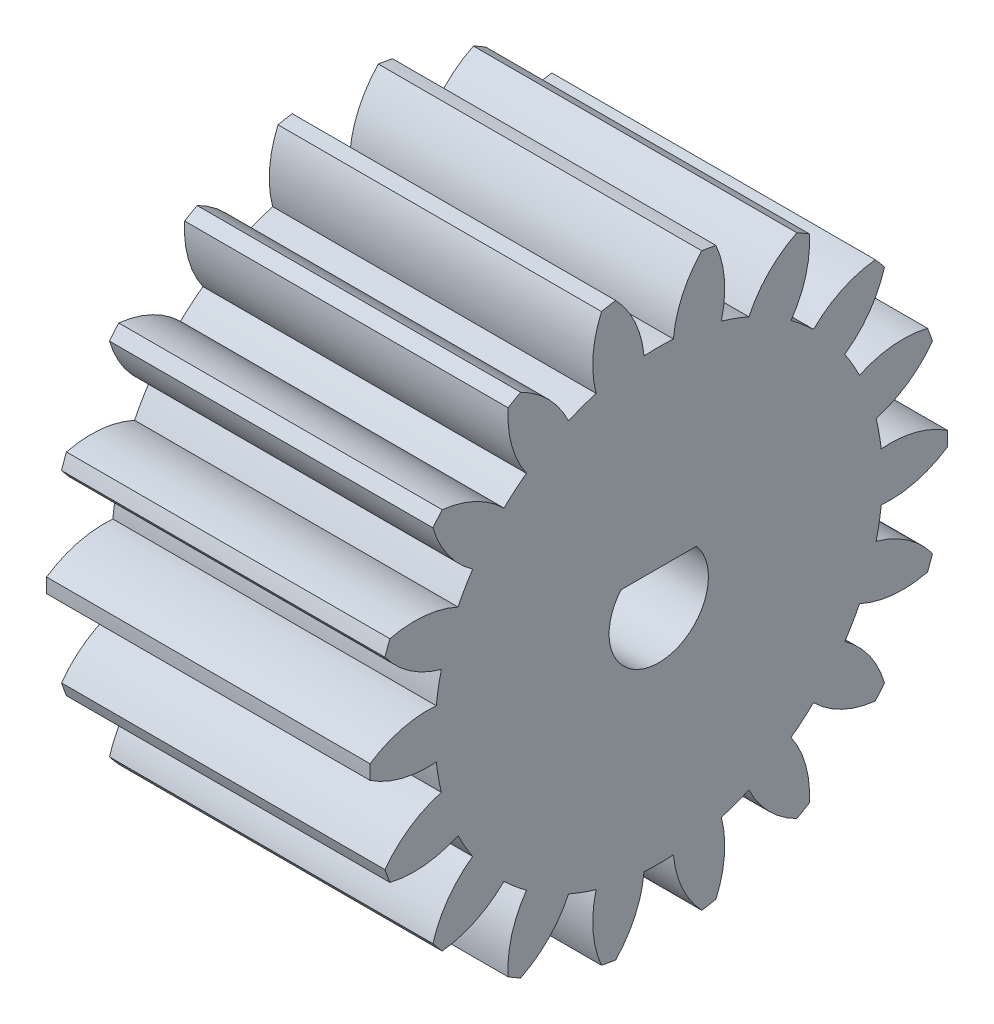
SolidWorks part; units mm, degrees
ref_plane "Plane1" through (0, 0, 0) normal (0, 0, 1) x (1, 0, 0)
ref_plane "Plane2" through (0, 0, 0) normal (0, 1, 0) x (1, 0, 0)
ref_plane "Plane3" through (0, 0, 0) normal (1, 0, 0) x (0, 0, -1)
other "Configuration Table"
sketch "HoldingSke" plane through (0, 0, 0) normal (0, 1, 0) x (1, 0, 0)
  line L0 (0, 0) -> (0.7608, -0.2472)
  line L1 (-15, 0) -> (100, 0) construction
  line L2 (0, 0) -> (-2.1039, 2.3779)
  line L3 (0, 0) -> (-11.863, 4.5341)
  line L4 (0, 0) -> (8.2133, 2.6687)
  line L5 (0, 0) -> (-46.8476, -17.4728)
  line L6 (0, 0) -> (-11.6055, -7.8303)
  line L7 (-2.1039, 2.3779) -> (8.6586, 51.2059)
  line L8 (-76.2, 54.61) -> (-76.1, 54.61)
  line L9 (-71.009, 38.7566) -> (-53.1078, 45.2721)
  line L10 (-76.2, 71.12) -> (104.1128, 71.12)
  line L11 (0, 0) -> (-14, 0)
  line L12 (-76.2, 101.6) -> (-76.155, 101.6)
  line L13 (24.9733, 27.94) -> (52.9518, 28.4284)
  line L14 (24.9733, 27.94) -> (24.9743, 27.94)
  line L15 (24.9733, 27.94) -> (100.4006, 29.5858)
  line L16 (-63.627, -1.25) -> (-12.827, -1.25)
  circle A0 centre (0, 0) radius 0.4
  circle A1 centre (0, 0) radius 9.6865
  circle A2 centre (0, 0) radius 37.5
  circle A3 centre (0, 0) radius 0.4
  dimension "MHD" = 19.373
  dimension "Hub_dia" = 75
  dimension "Bore" = 0.8
  dimension "MBD" = 0.8
  dimension "Num_teeth" = 18
  dimension "Pitch" = 0.8
  dimension "Overall_len" = 50
  dimension "Show_teeth" = 18
  dimension "Thickness" = 14
  dimension "OAL" = 50.0001
  dimension "T_dim" = 0.1
  dimension "Ap" = 20
  dimension "H" = 19.05
  dimension "Pitch_radius" = 180.3128
  dimension "Width" = 14
  dimension "Backlash" = 0.045
  dimension "Addendum_fac" = 1
  dimension "Dedendum_fac" = 1.25
  dimension "Clearance_fac" = 0.25
  dimension "Dedendum_add" = 0.001
  dimension "Module" = 1.25
sketch "BasProSke" plane through (0, 0, 0) normal (0, 1, 0) x (1, 0, 0)
  line L0 (-10, 0) -> (60, 0) construction
  line L1 (0, 0) -> (0, 12.5)
  line L2 (0, 0) -> (14, 0)
  line L3 (14, 0) -> (14, 12.5)
  line L4 (14, 12.5) -> (0, 12.5)
  dimension "Thickness" = 14
  dimension "Diameter" = 25
revolve "Base-Revolve" add sketch "BasProSke" angle 360 about L0
sketch "TooCutSke" plane through (0, 0, 0) normal (1, 0, 0) x (0, 0, -1)
  line L1 (0, 0) -> (0, 107) construction
  line L2 (0, 0) -> (-1.0592, 11.2) construction
  line L3 (0, 0) -> (-3.8945, 22.0869) construction
  line L4 (-1.0592, 11.2) -> (-1.9473, 11.0434) construction
  arc A0 (0.6346, 9.6657) -> (-0.6346, 9.6657) centre (0, 0) ccw
  arc A1 (1.8837, 12.3829) -> (-1.8837, 12.3829) centre (0, 0) ccw
  circle A2 centre (0, 0) radius 11.25 construction
  circle A3 centre (0, 0) radius 10.5715 construction
  arc A4 (-0.6346, 9.6657) -> (-1.8837, 12.3829) centre (-5.1154, 9.2515) ccw
  arc A5 (1.8837, 12.3829) -> (0.6346, 9.6657) centre (5.1154, 9.2515) ccw
  dimension "Root_dia" = 19.373
  dimension "Overcut_dia" = 25.0508
  dimension "Pitch_dia" = 22.5
  dimension "Base_dia" = 21.1431
  dimension "Flank_rad" = 4.5
  dimension "Half_ang" = 10
  dimension "Half_CT" = 0.9018
extrude "ToothCut" cut sketch "TooCutSke" along normal through all
fillet "Breaks" [suppressed] radius 0.025
fillet "RootFillets" [suppressed] radius 0.3135
pattern_circular "TeethCuts" count 18 over 360 about axis through (0, 0, 0) along (1, 0, 0) of "ToothCut", "RootFillets", "Breaks"
sketch "HubNeaOneSke" plane through (0, 0, 0) normal (-1, 0, 0) x (0, 0, 1)
  circle A0 centre (0, 0) radius 9.6865
  dimension "Diameter" = 19.373
extrude "HubNearOne" [suppressed] add sketch "HubNeaOneSke" along normal blind 36.0001
sketch "HubNeaBotSke" plane through (0, 0, 0) normal (-1, 0, 0) x (0, 0, 1)
  circle A0 centre (0, 0) radius 9.6865
  dimension "Diameter" = 19.373
extrude "HubNearBoth" [suppressed] add sketch "HubNeaBotSke" along normal blind 18
ref_plane "FarPln" through (14, 0, 0) normal (1, 0, 0) x (0, 0, -1)
sketch "HubFarSke" plane through (14, 0, 0) normal (1, 0, 0) x (0, 0, -1)
  circle A0 centre (0, 0) radius 9.6865
  dimension "Diameter" = 19.373
extrude "HubFar" [suppressed] add sketch "HubFarSke" along normal blind 18
sketch "BorSke" plane through (0, 0, 0) normal (1, 0, 0) x (0, 0, -1)
  circle A0 centre (0, 0) radius 0.4
  dimension "Diameter" = 0.8
extrude "Bore" cut sketch "BorSke" along normal mid plane 100.0001
sketch "KeySke" plane through (0, 0, 0) normal (1, 0, 0) x (0, 0, -1)
  line L0 (-0.05, 0) -> (-0.05, 0.5)
  line L1 (-0.05, 0.5) -> (0.05, 0.5)
  line L2 (0.05, 0.5) -> (0.05, 0)
  line L3 (0, 0) -> (0, 34) construction
  line L4 (-0.05, 0) -> (0.05, 0)
  dimension "Offset" = 0.5
  dimension "Width" = 0.1
extrude "Keyway" [suppressed] cut sketch "KeySke" along normal mid plane 100.0001
pattern_circular "Keyway2" [suppressed] count 2 every 90 about axis through (-10, 0, 0) along (1, 0, 0)
sketch "Croquis1" plane through (14, 0, 0) normal (1, 0, 0) x (0, 0, -1)
  line L0 (-1.6317, 1.4) -> (1.6317, 1.4)
  circle A0 centre (0, 0) radius 2.15
  point P5 (0, -2.15)
  point P6 (0, 1.4)
  dimension "D1" = 4.3
  dimension "D2" = 3.55
extrude "Cortar-Extruir1" cut sketch "Croquis1" against normal up to next contours L0 A0
equation "' \"Module@HoldingSke\" = 6.35"
equation "' \"Num_teeth@HoldingSke\" = 12"
equation "' \"Ap@HoldingSke\" =  20"
equation "' \"Ap@HoldingSke\" = 20"
equation "' \"Width@HoldingSke\" = 0.5 * 25.4"
equation "' \"Hub_dia@HoldingSke\"= 1 * 25.4"
equation "' \"Hub_dia@HoldingSke\" = 1 * 25.4"
equation "' \"Overall_len@HoldingSke\" = 1.0 * 25.4"
equation "' \"Bore@HoldingSke\" = 0.75 * 25.4"
equation "' \"T_dim@HoldingSke\" = 0.1 * 25.4"
equation "' \"Width@KeySke\" = 0.25 * 25.4"
equation "' \"Show_teeth@HoldingSke\" = 13"
equation "' \"Backlash@HoldingSke\" = 0.009 * 25.4"
equation "' \"Addendum_fac@HoldingSke\" = 1.0"
equation "' \"Dedendum_fac@HoldingSke\" = 1.25"
equation "' \"Dedendum_add@HoldingSke\" = 0.00005 * 25.4"
equation "' \"Clearance_fac@HoldingSke\" = 0.25"
equation "\"Pitch@HoldingSke\" = 1 / \"Module@HoldingSke\""
equation "\"Overcut_dia@TooCutSke\" = (\"Num_teeth@HoldingSke\" + 2 * \"Addendum_fac@HoldingSke\") / \"Pitch@HoldingSke\" + 0.002 * 25.4"
equation "\"Pitch_dia@TooCutSke\" = \"Num_teeth@HoldingSke\" / \"Pitch@HoldingSke\""
equation "\"Base_dia@TooCutSke\" = \"Num_teeth@HoldingSke\" / \"Pitch@HoldingSke\" * cos((\"Ap@HoldingSke\"  * 3.14159265 / 180))"
equation "\"Root_dia@TooCutSke\" = (\"Num_teeth@HoldingSke\" + 2) / \"Pitch@HoldingSke\" - 2 * (\"Addendum_fac@HoldingSke\" + \"Dedendum_fac@HoldingSke\") / \"Pitch@HoldingSke\" - \"Dedendum_add@HoldingSke\" * 2"
equation "\"Half_ang@TooCutSke\" = 180 / \"Num_teeth@HoldingSke\""
equation "\"Half_CT@TooCutSke\" = \"Num_teeth@HoldingSke\" / \"Pitch@HoldingSke\" * sin((3.14159265 / 2 / \"Num_teeth@HoldingSke\")) / 2 - 7 * \"Backlash@HoldingSke\" / 4"
equation "\"Flank_rad@TooCutSke\" = \"Num_teeth@HoldingSke\" / \"Pitch@HoldingSke\" / 5"
equation "\"Radius@RootFillets\" = \"Clearance_fac@HoldingSke\" / \"Pitch@HoldingSke\" + \"Dedendum_add@HoldingSke\""
equation "\"Break_rad@Breaks\" = 0.02 / \"Pitch@HoldingSke\""
equation "\"Thickness@HoldingSke\" = \"Width@HoldingSke\""
equation "\"OAL@HoldingSke\" = \"Thickness@HoldingSke\""
equation "\"MHD@HoldingSke\" = (\"Num_teeth@HoldingSke\" + 2) / \"Pitch@HoldingSke\" - 2 * (\"Addendum_fac@HoldingSke\" + \"Dedendum_fac@HoldingSke\")  / \"Pitch@HoldingSke\" - \"Dedendum_add@HoldingSke\" * 2"
equation "\"MBD@HoldingSke\" = (\"Num_teeth@HoldingSke\" + 2) / \"Pitch@HoldingSke\" - 2 * (\"Addendum_fac@HoldingSke\" + \"Dedendum_fac@HoldingSke\")  / \"Pitch@HoldingSke\" - \"Dedendum_add@HoldingSke\" * 2 - 0.002 * 25.4"
equation "\"MHD@HoldingSke\" = ((sgn( \"MHD@HoldingSke\" - \"Hub_dia@HoldingSke\" )-1)*( \"MHD@HoldingSke\" - \"Hub_dia@HoldingSke\" ))/-2+ \"Hub_dia@HoldingSke\""
equation "\"MBD@HoldingSke\" = ((sgn( \"MBD@HoldingSke\" - \"Bore@HoldingSke\" )-1)*( \"MBD@HoldingSke\" - \"Bore@HoldingSke\" ))/-2+ \"Bore@HoldingSke\""
equation "\"OAL@HoldingSke\" = ((sgn( \"OAL@HoldingSke\" - \"Overall_len@HoldingSke\" )+1)*( \"OAL@HoldingSke\" - \"Overall_len@HoldingSke\" ))/2 + \"Overall_len@HoldingSke\" + 0.000002 * 25.4"
equation "\"Num_teeth@TeethCuts\" = int( \"Show_teeth@HoldingSke\" ) + 1"
equation "\"Num_teeth@TeethCuts\" = ((sgn( \"Num_teeth@TeethCuts\" - \"Num_teeth@HoldingSke\" )-1)*( \"Num_teeth@TeethCuts\" - \"Num_teeth@HoldingSke\" ))/-2+ \"Num_teeth@HoldingSke\""
equation "\"Num_teeth@TeethCuts\" = ((sgn( \"Num_teeth@TeethCuts\" - 2.0)+1)*( \"Num_teeth@TeethCuts\" - 2.0))/2 +2.0"
equation "\"Angle@TeethCuts\" = 360.0 / \"Num_teeth@HoldingSke\""
equation "\"Diameter@BasProSke\" = (\"Num_teeth@HoldingSke\" + 2 * \"Addendum_fac@HoldingSke\") / \"Pitch@HoldingSke\""
equation "\"Thickness@BasProSke\"  = \"Thickness@HoldingSke\""
equation "' \"Fillet_rad@BasProSke\" =  \"Thickness@HoldingSke\" * 0.05"
equation "' \"Fillet_rad@BasProSke\" = \"Thickness@HoldingSke\" * 0.05"
equation "\"MHD@HoldingSke\" = ((sgn( \"MHD@HoldingSke\" - \"Root_dia@TooCutSke\" )-1)*( \"MHD@HoldingSke\" - \"Root_dia@TooCutSke\" ))/-2+ \"Root_dia@TooCutSke\""
equation "\"Diameter@HubNeaOneSke\" = \"MHD@HoldingSke\""
equation "\"Length@HubNearOne\" = \"OAL@HoldingSke\" - \"Thickness@BasProSke\""
equation "\"Diameter@HubNeaBotSke\" = \"MHD@HoldingSke\""
equation "\"Length@HubNearBoth\" = ( \"OAL@HoldingSke\" - \"Thickness@BasProSke\" ) / 2.0"
equation "\"Thickness@FarPln\" = \"Thickness@BasProSke\""
equation "\"Diameter@HubFarSke\" = \"MHD@HoldingSke\""
equation "\"Length@HubFar\" = ( \"OAL@HoldingSke\" - \"Thickness@BasProSke\" ) / 2.0"
equation "\"Diameter@BorSke\" = \"MBD@HoldingSke\""
equation "\"D1@Bore\" = \"OAL@HoldingSke\" * 2.0"
equation "\"D1@Keyway\" = \"OAL@HoldingSke\" * 2.0"
equation "\"Offset@KeySke\" = \"T_dim@HoldingSke\" + \"MBD@HoldingSke\" / 2.0"
